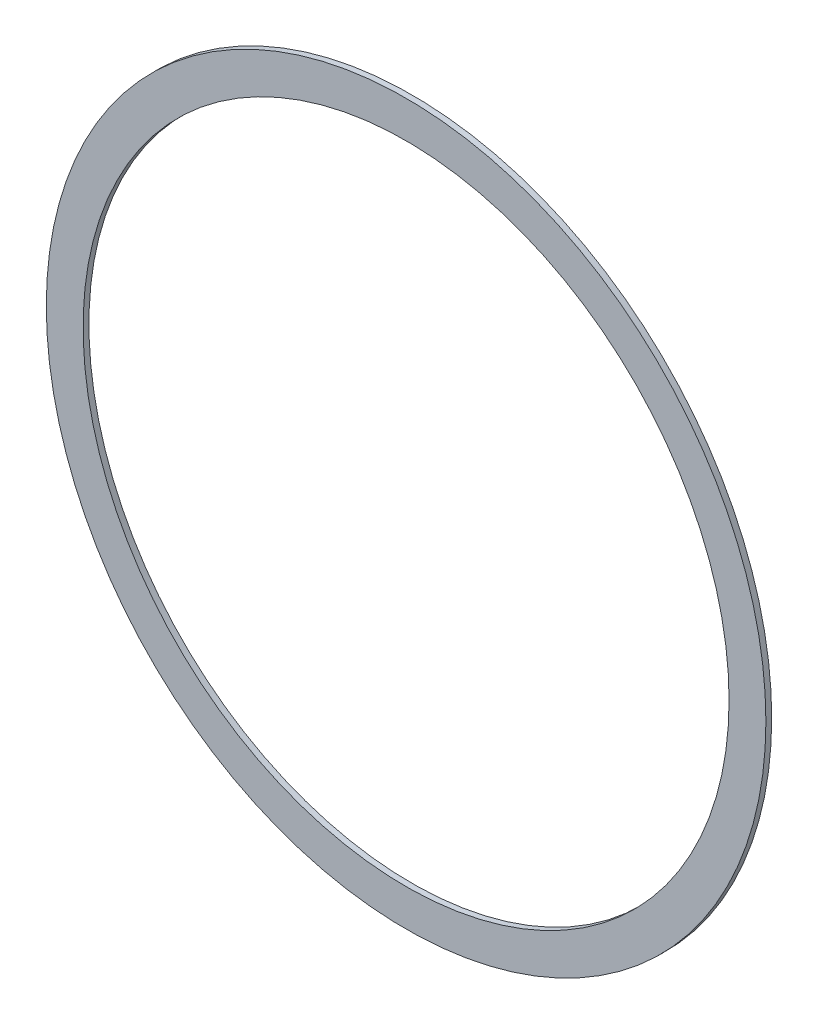
SolidWorks part; units mm, degrees
ref_plane "Front Plane" through (0, 0, 0) normal (0, 0, 1) x (1, 0, 0)
ref_plane "Top Plane" through (0, 0, 0) normal (0, 1, 0) x (1, 0, 0)
ref_plane "Right Plane" through (0, 0, 0) normal (1, 0, 0) x (0, 0, -1)
sketch "Sketch1" plane through (0, 0, 0) normal (0, 0, 1) x (1, 0, 0)
  circle A0 centre (0, 0) radius 250
  circle A1 centre (0, 0) radius 278.5
  dimension "D1" = 500
  dimension "D2" = 557
extrude "Boss-Extrude1" add sketch "Sketch1" along normal blind 4.5
